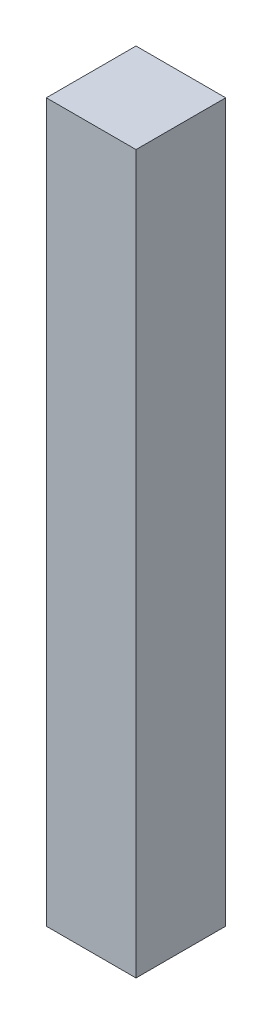
SolidWorks part; units mm, degrees
material "Pino"
ref_plane "Alzado" through (0, 0, 0) normal (0, 0, 1) x (1, 0, 0)
ref_plane "Planta" through (0, 0, 0) normal (0, 1, 0) x (1, 0, 0)
ref_plane "Vista lateral" through (0, 0, 0) normal (1, 0, 0) x (0, 0, -1)
sketch "Croquis2" plane through (0, 0, 0) normal (0, 0, 1) x (1, 0, 0)
  line L0 (0, 0) -> (5, 0)
  line L1 (5, 0) -> (5, 40)
  line L2 (5, 40) -> (0, 40)
  line L3 (0, 40) -> (0, 0)
  dimension "D1" = 40
  dimension "D2" = 5
extrude "Saliente-Extruir1" add sketch "Croquis2" along normal blind 5
